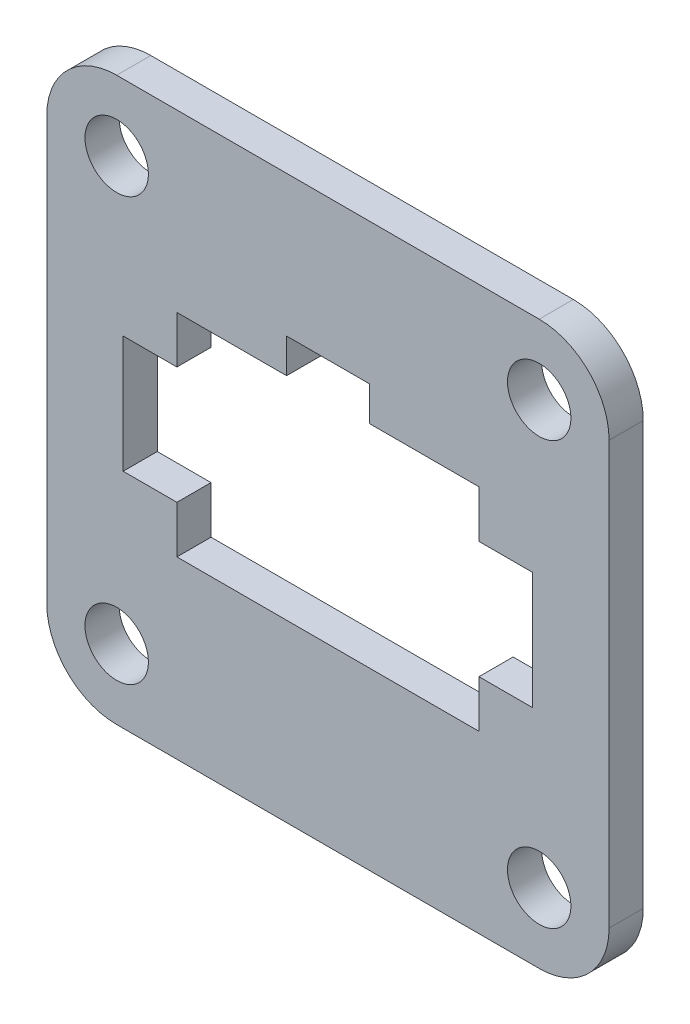
SolidWorks part; units mm, degrees
ref_plane "Front" through (0, 0, 0) normal (0, 0, 1) x (1, 0, 0)
ref_plane "Top" through (0, 0, 0) normal (0, 1, 0) x (1, 0, 0)
ref_plane "Right" through (0, 0, 0) normal (1, 0, 0) x (0, 0, -1)
sketch "Sketch1" plane through (0, 0, 0) normal (0, 0, 1) x (1, 0, 0)
  line L1 (0, 0) -> (26, 0)
  line L2 (0, 0) -> (0, 26)
  line L3 (0, 26) -> (26, 26)
  line L4 (26, 0) -> (26, 26)
  dimension "D1" = 26
  dimension "D2" = 26
extrude "Boss-Extrude1" add sketch "Sketch1" along normal blind 1.5875
sketch "Sketch2" plane through (0, 0, 1.5875) normal (0, 0, 1) x (1, 0, 0)
  line L0 (5.9, 8) -> (5.9, 10.2)
  line L1 (5.9, 18) -> (20.1, 18) construction
  line L2 (5.9, 18) -> (5.9, 8) construction
  line L3 (5.9, 8) -> (20.1, 8)
  line L4 (20.1, 18) -> (20.1, 8) construction
  line L5 (5.9, 10.2) -> (3.4, 10.2)
  line L6 (3.4, 10.2) -> (3.4, 15.8)
  line L7 (3.4, 15.8) -> (5.9, 15.8)
  line L8 (5.9, 15.8) -> (5.9, 18)
  line L9 (5.9, 18) -> (11, 18)
  line L10 (11, 18) -> (11, 19.6)
  line L11 (11, 19.6) -> (15, 19.6)
  line L12 (15, 19.6) -> (15, 18)
  line L13 (15, 18) -> (20.1, 18)
  line L14 (20.1, 18) -> (20.1, 15.8)
  line L15 (20.1, 15.8) -> (22.6, 15.8)
  line L16 (22.6, 15.8) -> (22.6, 10.2)
  line L17 (22.6, 10.2) -> (20.1, 10.2)
  line L18 (20.1, 10.2) -> (20.1, 8)
  line L19 (5.9, 18) -> (5.9, 26) construction
  line L20 (26, 26) -> (0, 26) construction
  line L21 (5.9, 8) -> (5.9, 0) construction
  line L22 (5.9, 8) -> (0, 8) construction
  line L23 (0, 26) -> (0, 0) construction
  line L24 (0, 0) -> (26, 0) construction
  line L25 (20.1, 8) -> (26, 8) construction
  line L26 (26, 0) -> (26, 26) construction
  dimension "D1" = 4
  dimension "D2" = 5.6
  dimension "D3" = 19.2
  dimension "D4" = 14.2
  dimension "D5" = 10
  dimension "D6" = 11.6
extrude "Cut-Extrude1" cut sketch "Sketch2" against normal through all
fillet "Fillet1" radius 3.175 4 edges at (0, 0, 0.7937) (26, 0, 0.7937) (26, 26, 0.7937) (0, 26, 0.7937)
sketch "Sketch5" plane through (0, 0, 1.5875) normal (0, 0, 1) x (1, 0, 0)
  circle A0 centre (3.175, 22.825) radius 1.55
  circle A1 centre (22.825, 22.825) radius 1.55
  circle A2 centre (22.825, 3.175) radius 1.55
  circle A3 centre (3.175, 3.175) radius 1.55
  dimension "D1" = 3.1
extrude "Cut-Extrude2" cut sketch "Sketch5" against normal through all
other "Move Face1" face at (24.7413, 1.2587, 0.7937) face at (26, 13, 0.7937) face at (13, 26, 0.7937) face at (24.7413, 24.7413, 0.7937) face at (1.2587, 24.7413, 0.7937) face at (0, 13, 0.7937) face at (13, 0, 0.7937) face at (1.2587, 1.2587, 0.7937) face at (4.725, 3.175, 0) face at (4.725, 22.825, 0) face at (24.375, 22.825, 0) face at (24.375, 3.175, 0) face at (21.35, 10.2, 0.7937) face at (4.65, 10.2, 0.7937) face at (5.9, 9.1, 0.7937) face at (3.4, 13, 0.7937) face at (5.9, 16.9, 0.7937) face at (11, 18.8, 0.7937) face at (13, 8, 0.7937) face at (20.1, 9.1, 0.7937) face at (22.6, 13, 0.7937) face at (20.1, 16.9, 0.7937) face at (15, 18.8, 0.7937) face at (13, 19.6, 0.7937) face at (4.65, 15.8, 0.7937) face at (8.45, 18, 0.7937) face at (17.55, 18, 0.7937) face at (21.35, 15.8, 0.7937) parameters "D1"=0.0762
